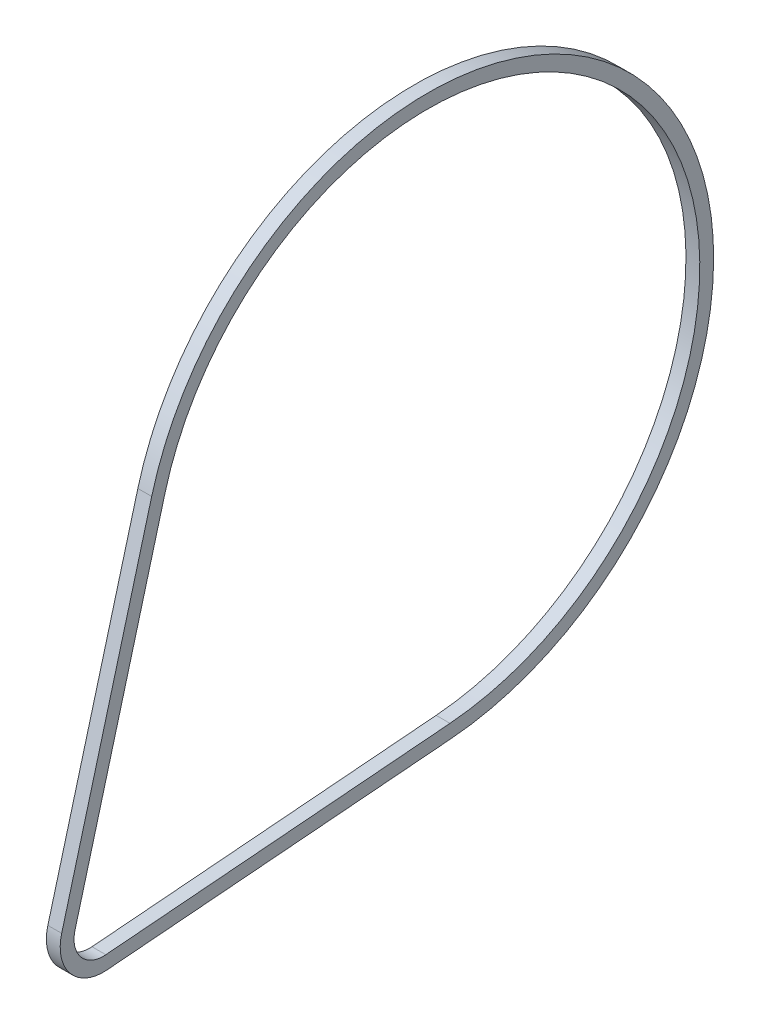
SolidWorks part; units mm, degrees
material "Plain Carbon Steel"
ref_plane "Front Plane" through (0, 0, 0) normal (0, 0, 1) x (1, 0, 0)
ref_plane "Top Plane" through (0, 0, 0) normal (0, 1, 0) x (1, 0, 0)
ref_plane "Right Plane" through (0, 0, 0) normal (1, 0, 0) x (0, 0, -1)
sketch "Sketch1" plane through (0, 0, 0) normal (1, 0, 0) x (0, 0, -1)
  line L0 (120.587, 167.1376) -> (87.5397, 44.7002)
  line L1 (104.1665, 24.7417) -> (230.5594, 35.1289)
  line L2 (125.4915, 165.8139) -> (92.4442, 43.3764)
  line L3 (103.7504, 29.8046) -> (230.1433, 40.1918)
  arc A0 (92.4442, 43.3764) -> (103.7504, 29.8046) centre (102.8662, 40.5633) ccw
  arc A1 (87.5397, 44.7002) -> (104.1665, 24.7417) centre (102.8662, 40.5633) ccw
  arc A2 (230.1433, 40.1918) -> (125.4915, 165.8139) centre (221.9593, 139.7761) ccw
  arc A3 (230.5594, 35.1289) -> (120.587, 167.1376) centre (221.9593, 139.7761) ccw
  arc A4 (314.6621, 90.4689) -> (316.1047, 93.2826) centre (221.9593, 139.7761) ccw construction
  arc A6 (114.6284, 37.0518) -> (112.9825, 33.6106) centre (114.4378, 35.0288) ccw construction
  dimension "D1" = 5.08
  dimension "D2" = 5.08
extrude "Boss-Extrude1" add sketch "Sketch1" along normal blind 5.08
